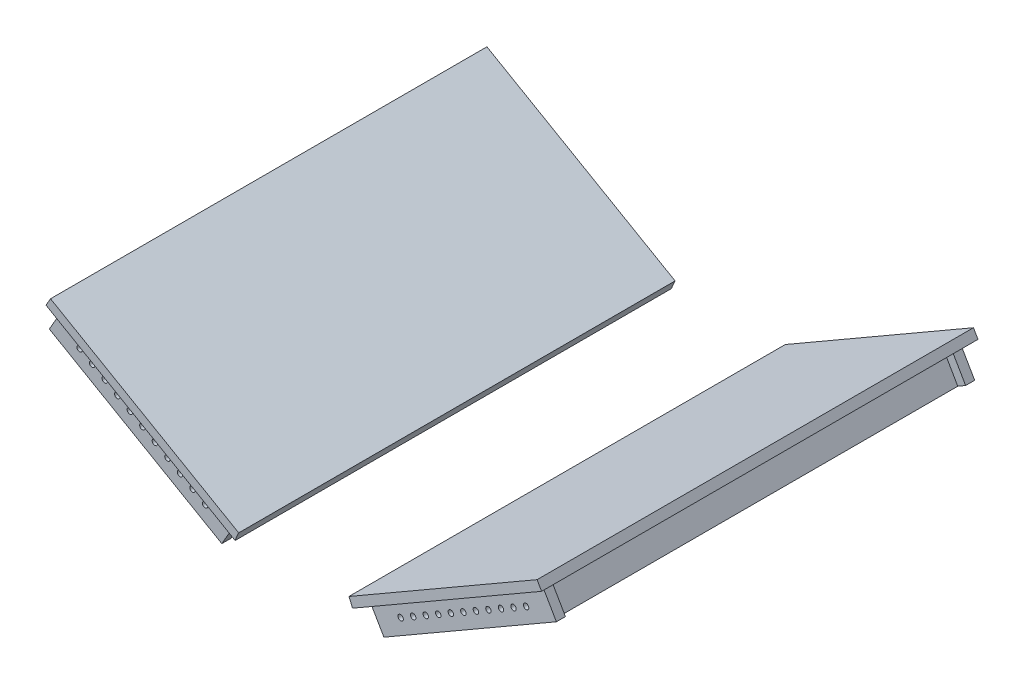
SolidWorks part; units mm, degrees
ref_plane "Front Plane" through (0, 0, 0) normal (0, 0, 1) x (1, 0, 0)
ref_plane "Top Plane" through (0, 0, 0) normal (0, 1, 0) x (1, 0, 0)
ref_plane "Right Plane" through (0, 0, 0) normal (1, 0, 0) x (0, 0, -1)
sketch "Sketch1" plane through (392.915, 557.3071, 808.8539) normal (0, 0, 1) x (1, 0, 0)
  line L0 (77.2843, 39.6634) -> (341.2488, 192.0634)
  line L1 (341.2488, 192.0634) -> (347.5988, 181.0649)
  line L2 (347.5988, 181.0649) -> (83.6343, 28.6649)
  line L3 (83.6343, 28.6649) -> (77.2843, 39.6634)
  line L4 (-77.2843, 39.6634) -> (-341.2488, 192.0634)
  line L5 (-341.2488, 192.0634) -> (-347.5988, 181.0649)
  line L6 (-347.5988, 181.0649) -> (-83.6343, 28.6649)
  line L7 (-83.6343, 28.6649) -> (-77.2843, 39.6634)
  dimension "D1" = 12.7
  dimension "D2" = 12.7
  dimension "D4" = 120
  dimension "D3" = 304.8
extrude "Boss-Extrude1" add sketch "Sketch1" along normal up to surface (273.05 mm away) and the other way up to surface (339.09 mm away)
sketch "Sketch2" plane through (331.0535, 573.4015, 0) normal (-0.5, -0.866, 0) x (0.866, -0.5, 0)
  line L0 (-317.241, 1069.2039) -> (-37.841, 1069.2039)
  line L1 (-317.241, 1056.5039) -> (-37.841, 1056.5039)
  line L2 (-317.241, 1056.5039) -> (-317.241, 1069.2039)
  line L3 (-37.841, 1056.5039) -> (-37.841, 1069.2039)
  line L4 (-329.941, 1081.9039) -> (-329.941, 469.7639) construction
  line L5 (-329.941, 1081.9039) -> (-25.141, 1081.9039) construction
  line L6 (-329.941, 775.8339) -> (-25.141, 775.8339) construction
  line L7 (-25.141, 1081.9039) -> (-25.141, 469.7639) construction
  line L8 (-317.241, 495.1639) -> (-37.841, 495.1639)
  line L9 (-317.241, 495.1639) -> (-317.241, 482.4639)
  line L10 (-317.241, 482.4639) -> (-37.841, 482.4639)
  line L11 (-37.841, 495.1639) -> (-37.841, 482.4639)
  dimension "D2" = 12.7
  dimension "D3" = 12.7
  dimension "D4" = 12.7
extrude "Boss-Extrude2" add sketch "Sketch2" along normal blind 38.1 separate body
sketch "Sketch3" plane through (331.0535, 573.4015, 0) normal (-0.5, -0.866, 0) x (0.866, -0.5, 0)
  line L0 (-50.541, 1056.5039) -> (-50.541, 495.1639)
  line L1 (-317.241, 1056.5039) -> (-37.841, 1056.5039) construction
  line L2 (-37.841, 495.1639) -> (-317.241, 495.1639) construction
  line L3 (-63.241, 1056.5039) -> (-63.241, 495.1639)
  line L4 (-50.541, 1056.5039) -> (-63.241, 1056.5039)
  line L5 (-50.541, 495.1639) -> (-63.241, 495.1639)
  line L6 (-25.141, 1081.9039) -> (-25.141, 469.7639) construction
  line L7 (-177.541, 1081.9039) -> (-177.541, 469.7639) construction
  line L8 (-329.941, 1081.9039) -> (-25.141, 1081.9039) construction
  line L9 (-25.141, 469.7639) -> (-329.941, 469.7639) construction
  line L10 (-304.541, 1056.5039) -> (-304.541, 495.1639)
  line L11 (-304.541, 1056.5039) -> (-291.841, 1056.5039)
  line L12 (-291.841, 1056.5039) -> (-291.841, 495.1639)
  line L13 (-304.541, 495.1639) -> (-291.841, 495.1639)
  dimension "D1" = 12.7
  dimension "D2" = 25.4
extrude "Boss-Extrude3" add sketch "Sketch3" along normal blind 38.1 separate body
sketch "Sketch4" plane through (0, 0, 1081.9039) normal (0, 0, 1) x (1, 0, 0)
  line L0 (315.6307, 596.9705) -> (470.1993, 596.9705) construction
  line L1 (470.1993, 596.9705) -> (476.5493, 585.972) construction
  line L2 (392.915, 596.9705) -> (392.915, 713.4156) construction
ref_plane "Plane1" through (392.915, 0, 0) normal (1, 0, 0) x (0, 0, -1)
mirror "Mirror1" about plane through (392.915, 0, 0) normal (1, 0, 0) of "Boss-Extrude2"
sketch "Sketch5" plane through (-134.596, 233.1271, 0) normal (0.5, -0.866, 0) x (0.866, 0.5, 0)
  line L0 (731.0898, 1056.5039) -> (731.0898, 495.1639)
  line L1 (997.7898, 1056.5039) -> (718.3898, 1056.5039) construction
  line L2 (718.3898, 495.1639) -> (997.7898, 495.1639) construction
  line L3 (743.7898, 1056.5039) -> (743.7898, 495.1639)
  line L4 (731.0898, 1056.5039) -> (743.7898, 1056.5039)
  line L5 (731.0898, 495.1639) -> (743.7898, 495.1639)
  line L6 (705.6898, 1081.9039) -> (705.6898, 469.7639) construction
  line L7 (858.0898, 1069.2039) -> (858.0898, 495.1639) construction
  line L8 (718.3898, 1069.2039) -> (997.7898, 1069.2039) construction
  line L9 (718.3898, 495.1639) -> (997.7898, 495.1639) construction
  line L10 (985.0898, 1056.5039) -> (985.0898, 495.1639)
  line L11 (985.0898, 1056.5039) -> (972.3898, 1056.5039)
  line L12 (972.3898, 1056.5039) -> (972.3898, 495.1639)
  line L13 (985.0898, 495.1639) -> (972.3898, 495.1639)
  dimension "D1" = 12.7
  dimension "D2" = 25.4
extrude "Boss-Extrude4" add sketch "Sketch5" along normal blind 38.1 separate body
sketch "Sketch6" plane through (-43.7698, 25.2705, 0) normal (0.866, -0.5, 0) x (0, 0, -1)
  line L0 (-775.8339, 662.107) -> (-775.8339, 624.007) construction
  line L1 (-1081.9039, 662.107) -> (-469.7639, 662.107) construction
  line L2 (-495.1639, 624.007) -> (-1056.5039, 624.007) construction
  line L3 (-634.2924, 630.357) -> (-609.5274, 655.757) construction
  line L8 (-788.526, 630.6744) -> (-762.8164, 655.757) construction
  line L9 (-788.2164, 655.757) -> (-763.4593, 630.3651) construction
  line L18 (-608.575, 630.6825) -> (-634.2924, 655.757) construction
  line L19 (-917.3754, 655.757) -> (-942.1404, 630.357) construction
  line L20 (-916.4865, 630.6825) -> (-942.2039, 655.757) construction
  line L21 (-1056.5039, 624.007) -> (-1056.5039, 662.107) construction
  circle A0 centre (-775.6712, 643.2157) radius 6.35
  circle A1 centre (-621.9099, 643.057) radius 6.35
  circle A2 centre (-929.7579, 643.057) radius 6.35
  point P6 (-775.8339, 643.057)
  dimension "D3" = 12.7
  dimension "D4" = 153.924
  dimension "D5" = 153.924
  dimension "D1" = 19.05
  dimension "D2" = 280.67
extrude "Cut-Extrude1" cut sketch "Sketch6" against normal up to surface (12.7 mm away) up to face at (266.7601, 588.5242, 775.8339)
sketch "Sketch7" plane through (633.1423, 365.5449, 0) normal (-0.866, -0.5, 0) x (0, 0, 1)
  line L0 (775.8339, 269.192) -> (775.8339, 231.092) construction
  line L1 (1056.5039, 269.192) -> (495.1639, 269.192) construction
  line L2 (1056.5039, 231.092) -> (495.1639, 231.092) construction
  line L8 (763.1419, 237.1246) -> (788.2164, 262.842) construction
  line L9 (762.8164, 262.842) -> (788.8434, 237.4497) construction
  line L17 (942.1404, 237.442) -> (916.7404, 262.842) construction
  line L18 (942.7754, 262.842) -> (916.7404, 237.442) construction
  line L19 (634.9274, 262.842) -> (608.8924, 237.442) construction
  line L20 (608.8924, 262.842) -> (634.2924, 237.442) construction
  line L21 (1081.9039, 269.192) -> (469.7639, 269.192) construction
  line L22 (621.9099, 250.142) -> (775.8339, 250.142) construction
  line L23 (775.8339, 250.142) -> (929.7579, 250.142) construction
  line L25 (1056.5039, 231.092) -> (1056.5039, 269.192) construction
  circle A0 centre (775.8339, 250.142) radius 6.35
  circle A1 centre (929.7579, 250.142) radius 6.35
  circle A2 centre (621.9099, 250.142) radius 6.35
  point P6 (775.8339, 250.142)
  dimension "D4" = 153.924
  dimension "D3" = 153.924
  dimension "D5" = 19.05
  dimension "D7" = 19.05
  dimension "D6" = 280.67
extrude "Cut-Extrude2" cut sketch "Sketch7" against normal up to surface (12.7 mm away) up to face at (519.0699, 588.5242, 775.8339)
sketch "Sketch8" plane through (0, 0, 1081.9039) normal (0, 0, 1) x (1, 0, 0)
  line L0 (200469.115, 557.3071) -> (-199683.285, 557.3071) construction
  line L1 (310.6423, 585.1863) -> (287.2837, 598.672) construction
  line L2 (310.6423, 585.1863) -> (303.7963, 589.1384)
  line L3 (45.3162, 738.372) -> (309.2807, 585.972) construction
  line L4 (315.6307, 596.9705) -> (309.2565, 600.6507)
  line L5 (315.6307, 596.9705) -> (51.6662, 749.3705) construction
  line L6 (309.2565, 600.6507) -> (303.7963, 589.1384)
  line L7 (475.1877, 585.1863) -> (498.5463, 598.672) construction
  line L8 (475.1877, 585.1863) -> (485.5529, 591.1702)
  line L9 (476.5493, 585.972) -> (740.5138, 738.372) construction
  line L10 (470.1993, 596.9705) -> (477.2299, 601.0296)
  line L11 (734.1638, 749.3705) -> (470.1993, 596.9705) construction
  line L12 (477.2299, 601.0296) -> (485.5529, 591.1702)
  arc A0 (315.6307, 596.9705) -> (310.6423, 585.1863) centre (392.915, 557.3071) ccw
  arc A1 (470.1993, 596.9705) -> (475.1877, 585.1863) centre (392.915, 557.3071) cw
extrude "Unnecessary Detail" add sketch "Sketch8" against normal up to surface (612.14 mm away) up to face at (180.4734, 667.6712, 469.7639)
sketch "Sketch9" plane through (0, 0, 1069.2039) normal (0, 0, 1) x (1, 0, 0)
  line L0 (255.7616, 594.8742) -> (79.7853, 696.4742) construction
  line L1 (392.915, 633.5071) -> (392.915, 481.1071) construction
  line L2 (279.2322, 559.3264) -> (37.2647, 699.0264) construction
  line L3 (37.2647, 699.0264) -> (56.3147, 732.022) construction
  circle A0 centre (255.7616, 594.8742) radius 3.81
  circle A1 centre (238.164, 605.0342) radius 3.81
  circle A2 centre (220.5664, 615.1942) radius 3.81
  circle A3 centre (202.9687, 625.3542) radius 3.81
  circle A4 centre (185.3711, 635.5142) radius 3.81
  circle A5 centre (167.7734, 645.6742) radius 3.81
  circle A6 centre (150.1758, 655.8342) radius 3.81
  circle A7 centre (132.5782, 665.9942) radius 3.81
  circle A8 centre (392.915, 557.3071) radius 76.2 construction
  circle A17 centre (114.9805, 676.1542) radius 3.81
  circle A18 centre (97.3829, 686.3142) radius 3.81
  circle A19 centre (79.7853, 696.4742) radius 3.81
  circle A20 centre (706.0447, 696.4742) radius 3.81
  circle A21 centre (688.4471, 686.3142) radius 3.81
  circle A22 centre (670.8495, 676.1542) radius 3.81
  circle A23 centre (653.2518, 665.9942) radius 3.81
  circle A24 centre (635.6542, 655.8342) radius 3.81
  circle A25 centre (618.0566, 645.6742) radius 3.81
  circle A26 centre (600.4589, 635.5142) radius 3.81
  circle A27 centre (582.8613, 625.3542) radius 3.81
  circle A28 centre (565.2637, 615.1942) radius 3.81
  circle A29 centre (547.666, 605.0342) radius 3.81
  circle A30 centre (530.0684, 594.8742) radius 3.81
  dimension "D3" = 19.05
  dimension "D4" = 38.1
extrude "Cut-Extrude3" cut sketch "Sketch9" against normal up to surface (586.74 mm away)
ref_plane "Plane2" through (0, 0, 775.8339) normal (0, 0, 1) x (1, 0, 0)
mirror "Mirror2" about plane through (0, 0, 775.8339) normal (0, 0, 1) of "Cut-Extrude3"
equation "\"WOOD_THICKNESS\"=0.5"
equation "\"D2@Sketch1\"=\"WOOD_THICKNESS\""
equation "\"TOP_SURFACE_WIDTH\"=12"
equation "\"D3@Sketch1\"=\"TOP_SURFACE_WIDTH\""
equation "\"SHORT_BEAM_LENGTH\"=11"
equation "\"D1@Sketch2\"=\"SHORT_BEAM_LENGTH\""
equation "\"D3@Sketch2\"=\"WOOD_THICKNESS\""
equation "\"SHORT_BEAM_TO_EDGE_CLEARANCE\"=0.5"
equation "\"D2@Sketch2\"=\"SHORT_BEAM_TO_EDGE_CLEARANCE\""
equation "\"D4@Sketch2\"=\"SHORT_BEAM_TO_EDGE_CLEARANCE\""
equation "\"D1@Sketch3\"=\"WOOD_THICKNESS\""
equation "\"LONG_BEAM_TO_EDGE_CLEARANCE\"=1"
equation "\"D2@Sketch3\"=\"LONG_BEAM_TO_EDGE_CLEARANCE\""
equation "\"D1@Sketch5\"=\"WOOD_THICKNESS\""
equation "\"D2@Sketch5\"=\"LONG_BEAM_TO_EDGE_CLEARANCE\""
equation "\"SCREW_HOLE_SPACING\"=6.06"
equation "\"D5@Sketch6\"=\"SCREW_HOLE_SPACING\""
equation "\"D4@Sketch6\"=\"SCREW_HOLE_SPACING\""
equation "\"BEAM_WIDTH\"= 1.5"
equation "\"D1@Boss-Extrude2\"=\"BEAM_WIDTH\""
equation "\"D1@Boss-Extrude3\"=\"BEAM_WIDTH\""
equation "\"D1@Boss-Extrude4\"=\"BEAM_WIDTH\""
equation "\"CENTER_SCREW_VERTICAL_ALIGNMENT\"=0.75"
equation "\"D4@Sketch7\"=\"SCREW_HOLE_SPACING\""
equation "\"D3@Sketch7\"=\"SCREW_HOLE_SPACING\""
equation "\"ALIGNMENT_HOLE_SPACING\"= 0.8"
equation "\"D2@Sketch9\"=\"ALIGNMENT_HOLE_SPACING\""
equation "\"ALIGNMENT_HOLE_VERTICAL_PLACEMENT\"=0.75"
equation "\"D3@Sketch9\"=\"ALIGNMENT_HOLE_VERTICAL_PLACEMENT\""
equation "\"ALIGNMENT_HOLE_ONE_HORIZONTAL_PLACEMENT\"=1.5"
equation "\"D4@Sketch9\"=\"ALIGNMENT_HOLE_ONE_HORIZONTAL_PLACEMENT\""
